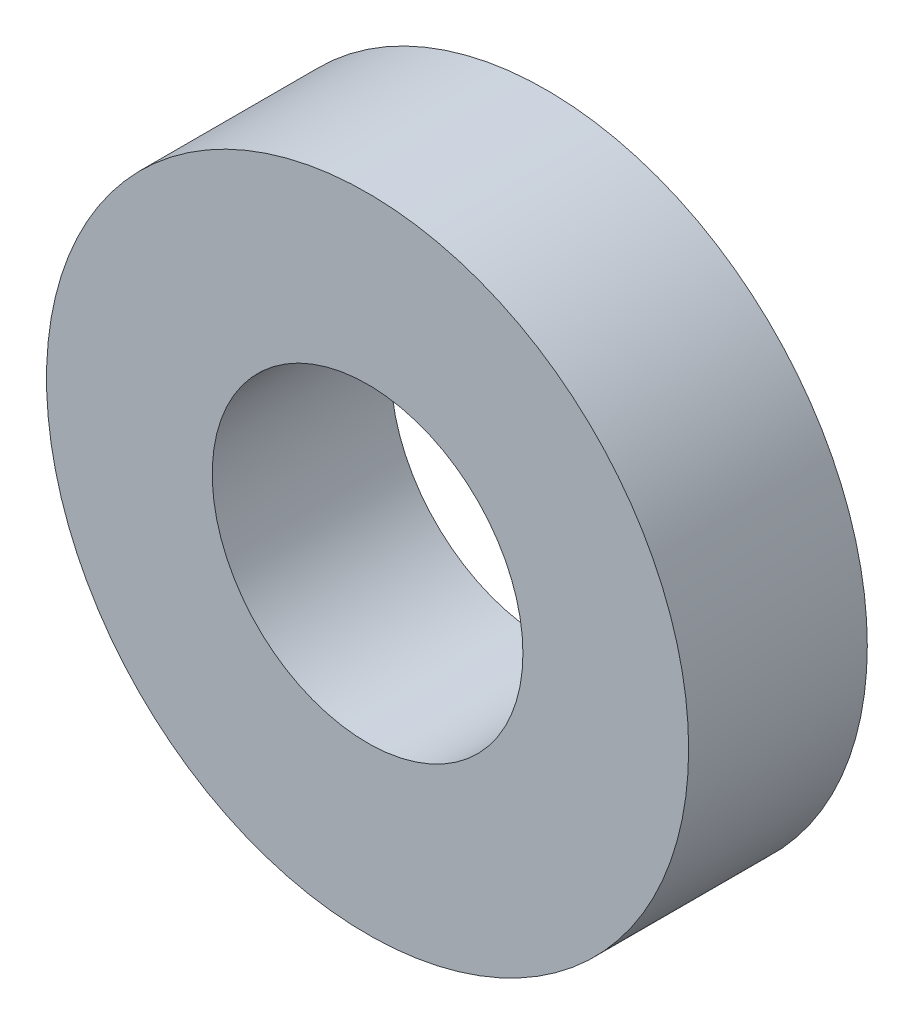
SolidWorks part; units mm, degrees
ref_plane "Front Plane" through (0, 0, 0) normal (0, 0, 1) x (1, 0, 0)
ref_plane "Top Plane" through (0, 0, 0) normal (0, 1, 0) x (1, 0, 0)
ref_plane "Right Plane" through (0, 0, 0) normal (1, 0, 0) x (0, 0, -1)
sketch "Sketch1" plane through (0, 0, 0) normal (0, 0, 1) x (1, 0, 0)
  circle A0 centre (0, 0) radius 15
  circle A1 centre (0, 0) radius 31
  dimension "D1" = 30
  dimension "D2" = 62
extrude "Boss-Extrude1" add sketch "Sketch1" along normal blind 17.25
